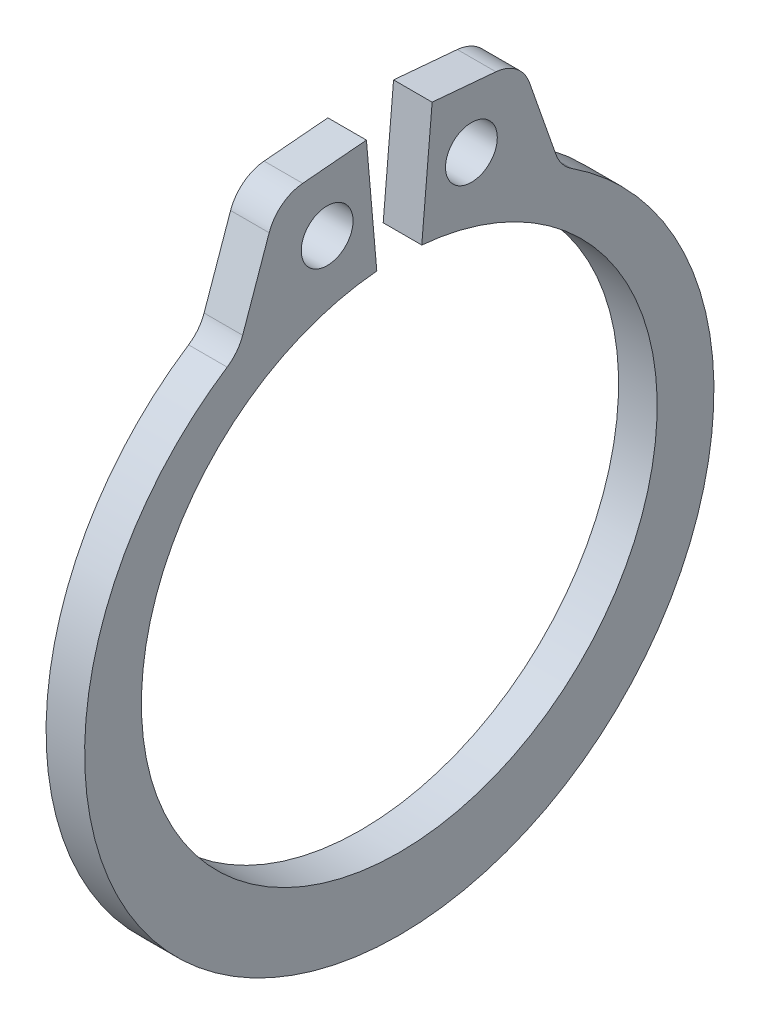
SolidWorks part; units mm, degrees
material "Cast Carbon Steel"
ref_plane "Front" through (0, 0, 0) normal (0, 0, 1) x (1, 0, 0)
ref_plane "Top" through (0, 0, 0) normal (0, 1, 0) x (1, 0, 0)
ref_plane "Right" through (0, 0, 0) normal (1, 0, 0) x (0, 0, -1)
sketch "Sketch1" plane through (0, 0, 0) normal (1, 0, 0) x (0, 0, -1)
  line L0 (0, 0) -> (0, 5.9436) construction
  line L1 (-0.518, 5.921) -> (-0.7571, 8.6537)
  line L2 (0.7571, 8.6537) -> (2.8067, 8.4744)
  line L3 (2.8067, 8.4744) -> (3.7141, 5.8857)
  line L4 (0.518, 5.921) -> (0.7571, 8.6537)
  line L5 (-0.7571, 8.6537) -> (-2.8067, 8.4744)
  line L6 (-2.8067, 8.4744) -> (-3.7141, 5.8857)
  line L7 (-3.7141, 5.8857) -> (-3.1719, 5.0265) construction
  line L8 (3.7141, 5.8857) -> (3.1719, 5.0265) construction
  line L9 (0, -5.9436) -> (0, -7.5946) construction
  line L10 (-2.8067, 8.4744) -> (-0.518, 5.921) construction
  line L11 (0, 5.9436) -> (0, 8.6868) construction
  line L12 (-5.9436, 0) -> (5.9436, 0) construction
  circle A0 centre (0, 0) radius 5.9436 construction
  arc A1 (-0.518, 5.921) -> (0.518, 5.921) centre (0, 0) ccw
  circle A3 centre (0, 0) radius 9.398 construction
  circle A4 centre (-1.6623, 7.1977) radius 0.5969
  circle A5 centre (1.6623, 7.1977) radius 0.5969
  arc A6 (-3.7141, 5.8857) -> (3.7141, 5.8857) centre (0, -0.3428) ccw
  point P0 (0, -7.5946)
  dimension "A" = 11.8872
  dimension "Hole" = 1.1938
  dimension "Smin" = 1.016
  dimension "H" = 2.7432
  dimension "D2" = 2.0574
  dimension "Angle" = 5
extrude "Extrude1" add sketch "Sketch1" along normal mid plane 0.889
fillet "Fillet1" radius 0.9017 4 edges at (0, 5.8857, 3.7141) (0, 5.8857, -3.7141) (0, 8.4744, 2.8067) (0, 8.4744, -2.8067)
sketch "Sketch2" plane through (0, 0, 0) normal (0, 0, 1) x (1, 0, 0)
  line L0 (-4.9403, 0) -> (12.8397, 0)
  line L1 (12.8397, 0) -> (12.8397, -6.35)
  line L2 (-0.4953, -6.35) -> (-4.5339, -6.35)
  line L3 (12.8397, -6.35) -> (0.4953, -6.35)
  line L4 (0.4953, -6.35) -> (0.4953, -5.9436)
  line L5 (0.4953, -5.9436) -> (-0.4953, -5.9436)
  line L6 (-0.4953, -5.9436) -> (-0.4953, -6.35)
  line L7 (-0.4953, -6.35) -> (-4.9403, -6.35) construction
  line L8 (-4.9403, -6.35) -> (-4.9403, 0) construction
  line L9 (12.8397, 0) -> (76.391, 0) construction
  line L10 (-4.5339, -6.35) -> (-4.9403, -5.9436)
  line L11 (-4.9403, -5.9436) -> (-4.9403, 0)
  point P10 (0, -5.9436)
  dimension "D2" = 17.78
  dimension "D3" = 4.445
  dimension "D1" = 45
revolve "Revolve1" [suppressed] add sketch "Sketch2" angle 360 about L9
delete or keep bodies "Body-Delete1" [suppressed] type delete bodies bodies 122
equation "\"D2@Sketch2\" = \"D1@Extrude1\"*20"
equation "\"D3@Sketch2\" = \"D2@Sketch2\"/4"
equation "\"D2@Sketch1\" = \"H@Sketch1\"*.75"
